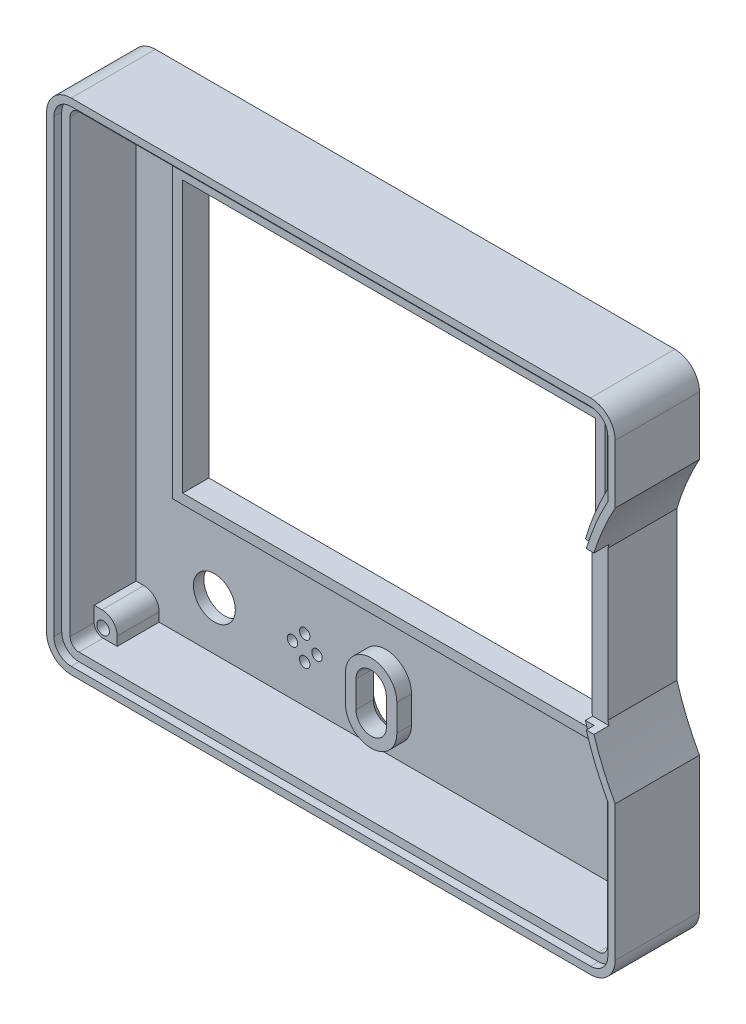
SolidWorks part; units mm, degrees
material "ABS"
ref_plane "Front Plane" through (0, 0, 0) normal (0, 0, 1) x (1, 0, 0)
ref_plane "Top Plane" through (0, 0, 0) normal (0, 1, 0) x (1, 0, 0)
ref_plane "Right Plane" through (0, 0, 0) normal (1, 0, 0) x (0, 0, -1)
sketch "Sketch1" plane through (0, 0, 0) normal (0, 0, 1) x (1, 0, 0)
  line L1 (-54.3, -47.7) -> (54.3, -47.7)
  line L2 (-54.3, -47.7) -> (-54.3, 47.7)
  line L3 (-54.3, 47.7) -> (54.3, 47.7)
  line L4 (54.3, -47.7) -> (54.3, 47.7)
  line L5 (-54.3, -47.7) -> (54.3, 47.7) construction
  line L6 (-54.3, 47.7) -> (54.3, -47.7) construction
  point P0 (0, 0)
  dimension "D1" = 108.6
  dimension "D2" = 95.4
extrude "Boss-Extrude1" add sketch "Sketch1" along normal blind 16.1
sketch "Sketch2" plane through (0, 0, 16.1) normal (0, 0, 1) x (1, 0, 0)
  line L0 (50.011, -6.8613) -> (50.011, 21.5821)
  line L1 (54.3, -47.7) -> (54.3, 47.7) construction
  line L2 (54.3, 47.7) -> (-54.3, 47.7) construction
  arc A0 (50.011, -6.8613) -> (50.011, 21.5821) centre (98.3107, 7.3604) ccw
  dimension "D1" = 100.7
  dimension "D2" = 4.289
  dimension "D3" = 40.3396
  dimension "D4" = 44.0108
extrude "Cut-Extrude1" cut sketch "Sketch2" against normal through all
fillet "Fillet1" radius 4.7 4 edges at (-54.3, -47.7, 8.05) (54.3, -47.7, 8.05) (-54.3, 47.7, 8.05) (54.3, 47.7, 8.05)
shell "Shell1" thickness 3
sketch "Sketch3" plane through (0, 0, 16.1) normal (0, 0, 1) x (1, 0, 0)
  line L5 (-51.3, 43) -> (-51.3, -43) construction
  line L6 (49.6, 44.7) -> (-49.6, 44.7) construction
  line L7 (51.3, 32.5837) -> (51.3, 43) construction
  line L8 (-49.6, -44.7) -> (49.6, -44.7) construction
  line L9 (51.3, -43) -> (51.3, -17.8628) construction
  line L10 (-51.3, 43) -> (-51.3, -43)
  line L11 (49.6, 44.7) -> (-49.6, 44.7)
  line L12 (51.3, 32.5837) -> (51.3, 43)
  line L13 (-49.6, -44.7) -> (49.6, -44.7)
  line L14 (51.3, -43) -> (51.3, -17.8628)
  line L20 (52.9, 32.1783) -> (52.9, 43)
  line L21 (49.6, 46.3) -> (-49.6, 46.3)
  line L22 (-52.9, 43) -> (-52.9, -43)
  line L23 (-49.6, -46.3) -> (49.6, -46.3)
  line L24 (52.9, -43) -> (52.9, -17.4574)
  line L25 (48.5495, 21.5689) -> (46.8876, 21.5689)
  line L26 (48.5495, -6.8481) -> (46.8876, -6.8481)
  arc A6 (-49.6, 44.7) -> (-51.3, 43) centre (-49.6, 43) ccw construction
  arc A7 (51.3, 43) -> (49.6, 44.7) centre (49.6, 43) ccw construction
  arc A8 (-51.3, -43) -> (-49.6, -44.7) centre (-49.6, -43) ccw construction
  arc A9 (49.6, -44.7) -> (51.3, -43) centre (49.6, -43) ccw construction
  arc A10 (51.3, 32.5837) -> (47.011, 22.0082) centre (98.3107, 7.3604) ccw construction
  arc A11 (47.011, -7.2874) -> (51.3, -17.8628) centre (98.3107, 7.3604) ccw construction
  arc A12 (-49.6, 44.7) -> (-51.3, 43) centre (-49.6, 43) ccw
  arc A13 (51.3, 43) -> (49.6, 44.7) centre (49.6, 43) ccw
  arc A14 (-51.3, -43) -> (-49.6, -44.7) centre (-49.6, -43) ccw
  arc A15 (49.6, -44.7) -> (51.3, -43) centre (49.6, -43) ccw
  arc A16 (51.3, 32.5837) -> (46.8876, 21.5689) centre (98.3107, 7.3604) ccw
  arc A17 (46.8876, -6.8481) -> (51.3, -17.8628) centre (98.3107, 7.3604) ccw
  arc A22 (52.9, 32.1783) -> (48.5495, 21.5689) centre (98.3107, 7.3604) ccw
  arc A23 (52.9, 43) -> (49.6, 46.3) centre (49.6, 43) ccw
  arc A24 (-49.6, 46.3) -> (-52.9, 43) centre (-49.6, 43) ccw
  arc A25 (-52.9, -43) -> (-49.6, -46.3) centre (-49.6, -43) ccw
  arc A26 (49.6, -46.3) -> (52.9, -43) centre (49.6, -43) ccw
  arc A27 (48.5495, -6.8481) -> (52.9, -17.4574) centre (98.3107, 7.3604) ccw
  arc A28 (51.3, 32.5837) -> (47.011, 22.0082) centre (98.3107, 7.3604) ccw construction
  arc A29 (47.011, -7.2874) -> (51.3, -17.8628) centre (98.3107, 7.3604) ccw construction
  dimension "D1" = 1.6
extrude "Cut-Extrude2" cut sketch "Sketch3" against normal blind 1.5
sketch "Sketch4" plane through (0, 0, 2) normal (0, 0, 1) x (1, 0, 0)
  line L0 (-54.3, 43) -> (-54.3, -43) construction
  line L1 (-39.4, 33.7) -> (39.4, 33.7)
  line L2 (-39.4, 33.7) -> (-39.4, -18.1)
  line L3 (-39.4, -18.1) -> (39.4, -18.1)
  line L4 (39.4, 33.7) -> (39.4, -18.1)
  line L5 (49.6, 47.7) -> (-49.6, 47.7) construction
  dimension "D1" = 78.8
  dimension "D2" = 51.8
  dimension "D3" = 14.9
  dimension "D4" = 14
extrude "Cut-Extrude3" cut sketch "Sketch4" against normal through all
sketch "Sketch5" plane through (0, 0, 2) normal (0, 0, 1) x (1, 0, 0)
  line L0 (39.4, 33.7) -> (-39.4, 33.7) construction
  line L1 (39.4, -18.1) -> (39.4, 33.7) construction
  line L2 (-39.4, -18.1) -> (39.4, -18.1) construction
  line L3 (-39.4, 33.7) -> (-39.4, -18.1) construction
  line L4 (39.4, 33.7) -> (-39.4, 33.7)
  line L5 (39.4, -18.1) -> (39.4, 33.7)
  line L6 (-39.4, -18.1) -> (39.4, -18.1)
  line L7 (-39.4, 33.7) -> (-39.4, -18.1)
  line L8 (41.3, 35.6) -> (-41.3, 35.6)
  line L9 (-41.3, 35.6) -> (-41.3, -20)
  line L10 (-41.3, -20) -> (41.3, -20)
  line L11 (41.3, -20) -> (41.3, 35.6)
  dimension "D1" = 1.9
extrude "Boss-Extrude2" add sketch "Sketch5" along normal blind 3
sketch "Sketch6" plane through (0, 0, 2) normal (0, 0, 1) x (1, 0, 0)
  line L0 (-3.6, -32.4628) -> (-3.6, -37.6) construction
  line L1 (-0.7, -32.4628) -> (-0.7, -37.6)
  line L2 (-6.5, -32.4628) -> (-6.5, -37.6)
  line L3 (-49.6, -47.7) -> (49.6, -47.7) construction
  line L4 (-54.3, 43) -> (-54.3, -43) construction
  line L5 (-21.4306, -35.0338) -> (-19.09, -32.6932) construction
  line L6 (-19.09, -32.6932) -> (-16.7494, -35.0338) construction
  line L7 (-16.7494, -35.0338) -> (-19.09, -37.3744) construction
  line L8 (-19.09, -37.3744) -> (-21.4306, -35.0338) construction
  circle A0 centre (-36.35, -35.4) radius 4
  circle A1 centre (-19.09, -32.6932) radius 1
  circle A2 centre (-19.09, -37.3744) radius 1
  circle A3 centre (-21.4306, -35.0338) radius 1
  circle A4 centre (-16.7494, -35.0338) radius 1
  arc A5 (-0.7, -32.4628) -> (-6.5, -32.4628) centre (-3.6, -32.4628) ccw
  arc A6 (-6.5, -37.6) -> (-0.7, -37.6) centre (-3.6, -37.6) ccw
  point P12 (-3.6, -35.0314)
  dimension "D1" = 8
  dimension "D2" = 2
  dimension "D5" = 10.1
  dimension "D6" = 50.7
  dimension "D7" = 10.3256
  dimension "D8" = 35.21
  dimension "D9" = 4.6812
  dimension "D10" = 12.3
  dimension "D11" = 17.95
  dimension "D3" = 5.8
  dimension "D4" = 5.1372
extrude "Cut-Extrude4" cut sketch "Sketch6" against normal through all
sketch "Sketch7" plane through (0, 0, 2) normal (0, 0, 1) x (1, 0, 0)
  line L0 (-6.5, -32.4628) -> (-6.5, -37.6) construction
  line L1 (-0.7, -37.6) -> (-0.7, -32.4628) construction
  line L2 (-6.5, -32.4628) -> (-6.5, -37.6)
  line L3 (-0.7, -37.6) -> (-0.7, -32.4628)
  line L4 (-8.5, -32.4628) -> (-8.5, -37.6)
  line L5 (1.3, -37.6) -> (1.3, -32.4628)
  arc A0 (-0.7, -32.4628) -> (-6.5, -32.4628) centre (-3.6, -32.4628) ccw construction
  arc A1 (-6.5, -37.6) -> (-0.7, -37.6) centre (-3.6, -37.6) ccw construction
  arc A2 (-0.7, -32.4628) -> (-6.5, -32.4628) centre (-3.6, -32.4628) ccw
  arc A3 (-6.5, -37.6) -> (-0.7, -37.6) centre (-3.6, -37.6) ccw
  arc A4 (-8.5, -37.6) -> (1.3, -37.6) centre (-3.6, -37.6) ccw
  arc A5 (1.3, -32.4628) -> (-8.5, -32.4628) centre (-3.6, -32.4628) ccw
  dimension "D1" = 2
extrude "Boss-Extrude3" add sketch "Sketch7" along normal blind 2.8
chamfer "Chamfer1" distance 1.5 angle 45 4 edges at (-0.7, -35.0314, 0) (-3.6, -29.5628, 0) (-3.6, -40.5, 0) (-6.5, -35.0314, 0)
sketch "Sketch8" plane through (54.3, 0, 0) normal (1, 0, 0) x (0, 0, -1)
  line L0 (-16.1, -43) -> (-16.1, -17.0972) construction
  line L1 (-16.1, -7.6396) -> (-13.2, -7.6396)
  line L2 (-16.1, -7.6396) -> (-16.1, 22.3604)
  line L3 (-16.1, 22.3604) -> (-13.2, 22.3604)
  line L4 (-13.2, -7.6396) -> (-13.2, 22.3604)
  line L5 (0, 7.3604) -> (-13.2, 7.3604) construction
  line L6 (0, 21.5821) -> (0, -6.8613) construction
  dimension "D1" = 30
  dimension "D2" = 2.9
extrude "Cut-Extrude5" cut sketch "Sketch8" against normal up to next
sketch "Sketch9" plane through (0, 0, 2) normal (0, 0, 1) x (1, 0, 0)
  line L0 (49.6, 44.7) -> (-49.6, 44.7) construction
  line L1 (51.3, 32.5837) -> (51.3, 43) construction
  line L2 (49.6, 44.7) -> (46.9, 44.7)
  line L3 (-51.3, 40.1) -> (-46.9, 40.1)
  line L4 (-46.9, 44.7) -> (-46.9, 40.1)
  line L5 (51.3, 40.1) -> (51.3, 43)
  line L6 (-51.3, -43) -> (-51.3, 43) construction
  line L7 (51.3, 40.1) -> (46.9, 40.1)
  line L8 (46.9, 44.7) -> (46.9, 40.1)
  line L9 (-51.3, -43) -> (-51.3, -40.1)
  line L10 (49.6, -44.7) -> (46.9, -44.7)
  line L11 (51.3, -40.1) -> (46.9, -40.1)
  line L12 (46.9, -44.7) -> (46.9, -40.1)
  line L13 (51.3, -43) -> (51.3, -17.8628) construction
  line L14 (51.3, -43) -> (51.3, -40.1)
  line L15 (-51.3, -40.1) -> (-46.9, -40.1)
  line L16 (-46.9, -44.7) -> (-46.9, -40.1)
  line L17 (-51.3, 43) -> (-51.3, -43) construction
  line L18 (49.6, -44.7) -> (-49.6, -44.7) construction
  line L19 (51.3, -17.8628) -> (51.3, -43) construction
  line L20 (-46.9, -44.7) -> (-49.6, -44.7)
  line L21 (-51.3, 40.1) -> (-51.3, 43)
  line L22 (-46.9, 44.7) -> (-49.6, 44.7)
  arc A0 (51.3, 43) -> (49.6, 44.7) centre (49.6, 43) ccw construction
  arc A1 (51.3, 43) -> (49.6, 44.7) centre (49.6, 43) ccw
  arc A2 (-49.6, 44.7) -> (-51.3, 43) centre (-49.6, 43) ccw construction
  arc A3 (-49.6, 44.7) -> (-51.3, 43) centre (-49.6, 43) ccw
  arc A4 (-51.3, -43) -> (-49.6, -44.7) centre (-49.6, -43) ccw construction
  arc A5 (-51.3, -43) -> (-49.6, -44.7) centre (-49.6, -43) ccw
  arc A6 (49.6, -44.7) -> (51.3, -43) centre (49.6, -43) ccw construction
  arc A7 (49.6, -44.7) -> (51.3, -43) centre (49.6, -43) ccw
  dimension "D1" = 4.6
  dimension "D2" = 4.4
  dimension "D3" = 4.6
  dimension "D4" = 4.4
extrude "Boss-Extrude4" add sketch "Sketch9" along normal blind 8
fillet "Fillet2" radius 2.9 4 edges at (-46.9, 40.1, 6) (46.9, 40.1, 6) (46.9, -40.1, 6) (-46.9, -40.1, 6)
sketch "Sketch10" plane through (0, 0, 10) normal (0, 0, 1) x (1, 0, 0)
  line L0 (-54.3, 43) -> (-54.3, -43) construction
  line L1 (49.6, 47.7) -> (-49.6, 47.7) construction
  line L2 (-49.6, -47.7) -> (49.6, -47.7) construction
  line L3 (54.3, -43) -> (54.3, -17.0972) construction
  circle A0 centre (-49.6, 43) radius 1.21
  circle A1 centre (49.6, 43) radius 1.21
  circle A2 centre (49.6, -43) radius 1.21
  circle A3 centre (-49.6, -43) radius 1.21
  dimension "D1" = 2.42
  dimension "D2" = 4.7
  dimension "D3" = 4.7
  dimension "D4" = 4.7
  dimension "D5" = 4.7
extrude "Cut-Extrude6" cut sketch "Sketch10" against normal blind 9
